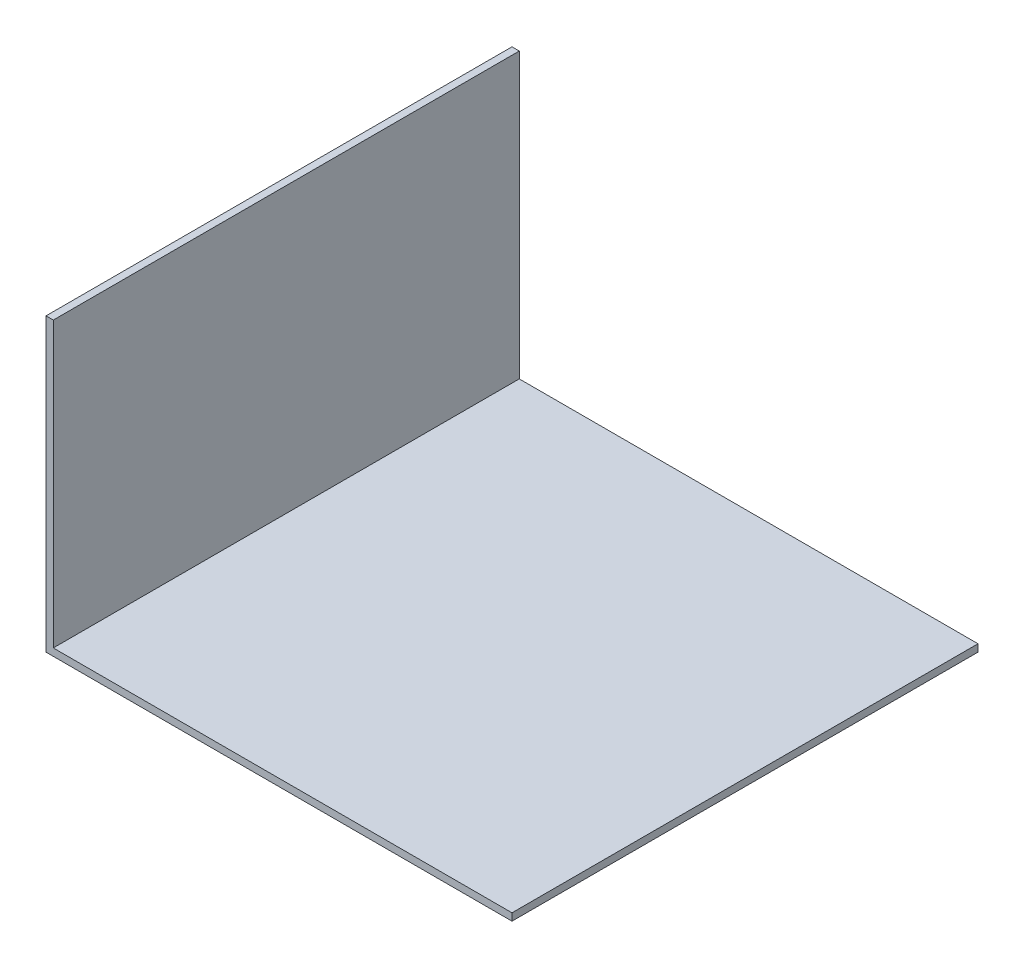
SolidWorks part; units mm, degrees
material "Glass"
ref_plane "Front Plane" through (0, 0, 0) normal (0, 0, 1) x (1, 0, 0)
ref_plane "Top Plane" through (0, 0, 0) normal (0, 1, 0) x (1, 0, 0)
ref_plane "Right Plane" through (0, 0, 0) normal (1, 0, 0) x (0, 0, -1)
sketch "Sketch2" plane through (0, 0, 0) normal (0, 0, 1) x (1, 0, 0)
  line L1 (21.1133, 21.7856) -> (224.3133, 21.7856)
  line L2 (21.1133, 21.7856) -> (21.1133, 148.7856)
  line L3 (21.1133, 148.7856) -> (224.3133, 148.7856)
  line L4 (224.3133, 21.7856) -> (224.3133, 148.7856)
  line L5 (224.3133, 148.7856) -> (24.2883, 148.7856)
  line L6 (224.3133, 148.7856) -> (224.3133, 24.9606)
  line L7 (224.3133, 24.9606) -> (24.2883, 24.9606)
  line L8 (24.2883, 148.7856) -> (24.2883, 24.9606)
  dimension "D1" = 3.175
  dimension "D2" = 3.175
  dimension "D3" = 203.2
  dimension "D4" = 127
extrude "Boss-Extrude1" add sketch "Sketch2" along normal blind 203.2 contours L8 L3 L2 L1 L4 L7
